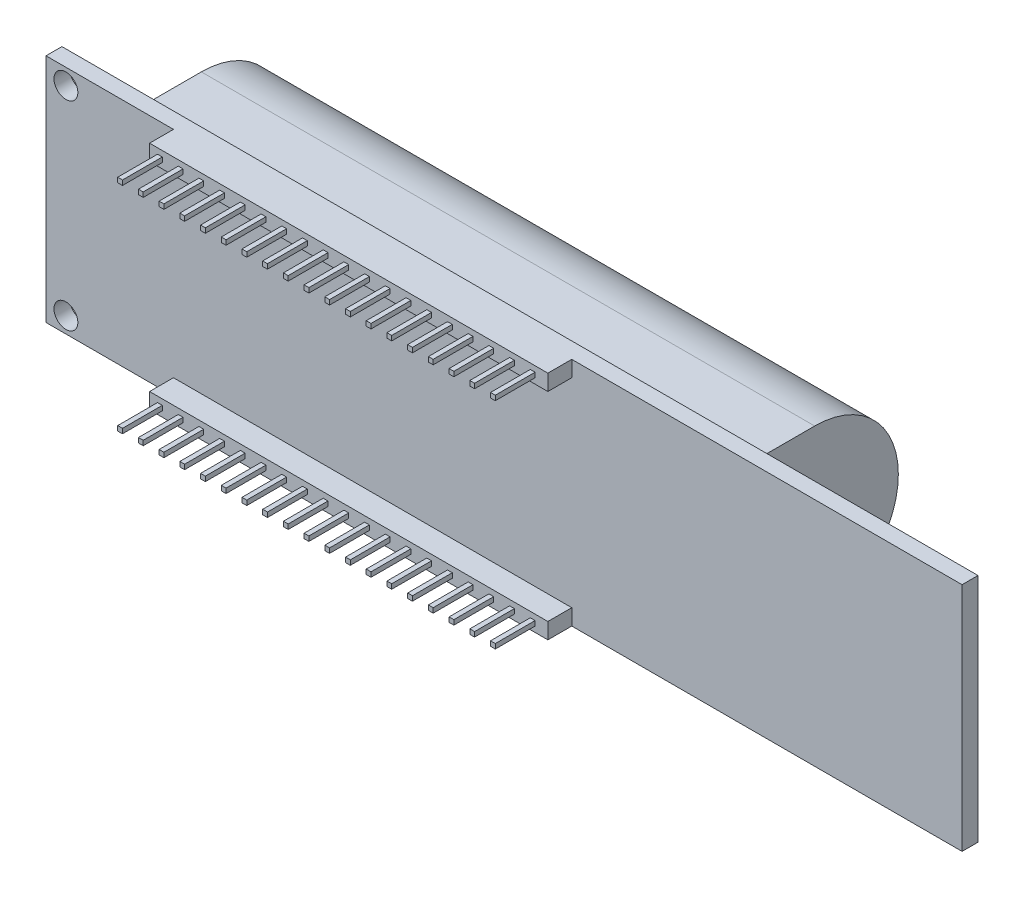
SolidWorks part; units mm, degrees
ref_plane "Plan de face" through (0, 0, 0) normal (0, 0, 1) x (1, 0, 0)
ref_plane "Plan de dessus" through (0, 0, 0) normal (0, 1, 0) x (1, 0, 0)
ref_plane "Plan de droite" through (0, 0, 0) normal (1, 0, 0) x (0, 0, -1)
sketch "Esquisse1" plane through (0, 0, 0) normal (0, 0, 1) x (1, 0, 0)
  line L1 (-57.5, -14.5) -> (57.5, -14.5)
  line L2 (-57.5, -14.5) -> (-57.5, 14.5)
  line L3 (-57.5, 14.5) -> (57.5, 14.5)
  line L4 (57.5, -14.5) -> (57.5, 14.5)
  line L5 (-57.5, -14.5) -> (57.5, 14.5) construction
  line L6 (-57.5, 14.5) -> (57.5, -14.5) construction
  point P0 (0, 0)
  dimension "D1" = 29
  dimension "D2" = 115
extrude "Boss.-Extru.1" add sketch "Esquisse1" along normal blind 2 contours L3 L4 L1 L2
sketch "Esquisse2" plane through (0, 0, 0) normal (0, 0, -1) x (-1, 0, 0)
  line L0 (57.5, 14.5) -> (-57.5, 14.5) construction
  line L1 (57.5, -14.5) -> (57.5, 14.5) construction
  circle A0 centre (55, 12.5) radius 1.5
  point P6 (67.121, 6.2187)
  point P7 (56.7586, 9.2888)
  dimension "D1" = 3
  dimension "D2" = 2
  dimension "D3" = 2.5
extrude "Enlèv. mat.-Extru.1" cut sketch "Esquisse2" against normal up to next
mirror "Symétrie1" about plane through (0, 0, 0) normal (0, 1, 0) of "Enlèv. mat.-Extru.1"
sketch "Esquisse3" plane through (0, 0, 0) normal (0, 0, -1) x (-1, 0, 0)
  line L0 (57.5, -14.5) -> (57.5, 14.5) construction
  line L1 (-27, 10.5) -> (50, 10.5)
  line L2 (-27, 10.5) -> (-27, -10.5)
  line L3 (-27, -10.5) -> (50, -10.5)
  line L4 (50, 10.5) -> (50, -10.5)
  point P4 (-27, 0)
  dimension "D1" = 21
  dimension "D2" = 7.5
  dimension "D3" = 77
extrude "Boss.-Extru.2" add sketch "Esquisse3" along normal blind 10
sketch "Esquisse4" plane through (27, 0, 0) normal (1, 0, 0) x (0, 0, -1)
  line L0 (10, 10.5) -> (10, -10.5) construction
  line L1 (10, 10.5) -> (10, -10.5)
  arc A0 (10, -10.5) -> (10, 10.5) centre (10, 0) ccw
extrude "Boss.-Extru.3" add sketch "Esquisse4" against normal up to surface (77 mm away) up to face at (-50, 0, -5)
sketch "Esquisse5" plane through (0, 0, 2) normal (0, 0, 1) x (1, 0, 0)
  line L0 (-57.5, 14.5) -> (57.5, 14.5) construction
  line L1 (-41.4983, 14.5) -> (8.5017, 14.5)
  line L2 (-41.4983, 14.5) -> (-41.4983, 12.5)
  line L3 (-41.4983, 12.5) -> (8.5017, 12.5)
  line L4 (8.5017, 14.5) -> (8.5017, 12.5)
  dimension "D1" = 2
  dimension "D2" = 50
extrude "Boss.-Extru.4" add sketch "Esquisse5" along normal blind 8
sketch "Esquisse6" plane through (0, 14.5, 0) normal (0, 1, 0) x (1, 0, 0)
  line L0 (8.5017, -10) -> (-41.4983, -10) construction
  line L1 (-41.4983, -10) -> (-40.4983, -10)
  line L2 (-41.4983, -10) -> (-41.4983, -5)
  line L3 (-41.4983, -5) -> (-40.4983, -5)
  line L4 (-40.4983, -10) -> (-40.4983, -5)
  line L5 (-41.4983, -10) -> (-41.4983, -2) construction
  dimension "D1" = 1
  dimension "D2" = 5
extrude "Enlèv. mat.-Extru.2" cut sketch "Esquisse6" against normal up to next
sketch "Esquisse8" plane through (-40.4983, 0, 0) normal (-1, 0, 0) x (0, 0, 1)
  line L0 (10, 12.5) -> (10, 14.5) construction
  line L1 (5, 14.5) -> (10, 14.5)
  line L2 (5, 14.5) -> (5, 13.8)
  line L3 (5, 13.8) -> (10, 13.8)
  line L4 (10, 14.5) -> (10, 13.8)
  line L5 (7.5, 13.8) -> (7.5, 13.2) construction
  line L6 (10, 13.2) -> (5, 13.2)
  line L7 (10, 13.2) -> (10, 12.5)
  line L8 (10, 12.5) -> (5, 12.5)
  line L9 (5, 13.2) -> (5, 12.5)
  line L10 (7.5, 14.5) -> (7.5, 12.5) construction
  point P14 (7.5, 13.5)
  point P17 (7.5, 13.5)
  dimension "D1" = 0.6
extrude "Enlèv. mat.-Extru.4" cut sketch "Esquisse8" against normal up to next
sketch "Esquisse7" plane through (0, 14.5, 0) normal (0, 1, 0) x (1, 0, 0)
  line L0 (8.5017, -10) -> (-40.4983, -10) construction
  line L1 (-39.8983, -10) -> (-37.8983, -10)
  line L2 (-39.8983, -10) -> (-39.8983, -5)
  line L3 (-39.8983, -5) -> (-37.8983, -5)
  line L4 (-37.8983, -10) -> (-37.8983, -5)
  line L5 (-40.4983, -10) -> (-40.4983, -5) construction
  line L6 (8.5017, -5) -> (-41.4983, -5) construction
  point P10 (-16.4983, -5)
  dimension "D1" = 0.6
  dimension "D2" = 2
extrude "Enlèv. mat.-Extru.3" cut sketch "Esquisse7" against normal up to next
pattern_linear "Répétition linéaire1" count 19 spacing 2.6 along (1, 0, 0) of "Enlèv. mat.-Extru.3"
mirror "Symétrie2" about plane through (0, 0, 0) normal (0, 1, 0) of "Enlèv. mat.-Extru.4", "Répétition linéaire1", "Enlèv. mat.-Extru.3", "Enlèv. mat.-Extru.2", "Boss.-Extru.4"
